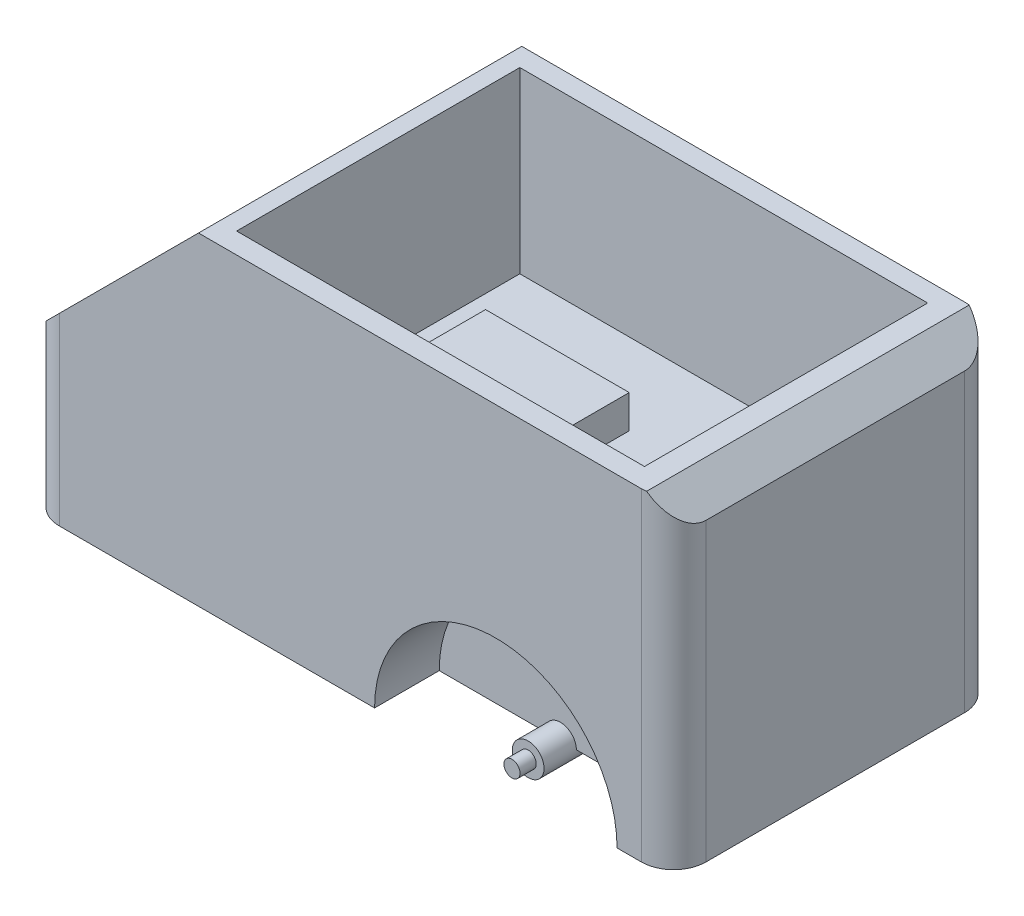
SolidWorks part; units mm, degrees
ref_plane "Front Plane" through (0, 0, 0) normal (0, 0, 1) x (1, 0, 0)
ref_plane "Top Plane" through (0, 0, 0) normal (0, 1, 0) x (1, 0, 0)
ref_plane "Right Plane" through (0, 0, 0) normal (1, 0, 0) x (0, 0, -1)
sketch "Sketch1" plane through (0, 0, 0) normal (0, 1, 0) x (1, 0, 0)
  line L1 (-91.44, 50.8) -> (91.44, 50.8)
  line L2 (-101.6, 40.64) -> (-101.6, -40.64)
  line L3 (-91.44, -50.8) -> (91.44, -50.8)
  line L4 (101.6, 40.64) -> (101.6, -40.64)
  line L5 (-101.6, 50.8) -> (101.6, -50.8) construction
  line L6 (-101.6, -50.8) -> (101.6, 50.8) construction
  arc A0 (91.44, 50.8) -> (101.6, 40.64) centre (91.44, 40.64) cw
  arc A1 (91.44, -50.8) -> (101.6, -40.64) centre (91.44, -40.64) ccw
  arc A2 (-101.6, -40.64) -> (-91.44, -50.8) centre (-91.44, -40.64) ccw
  arc A3 (-91.44, 50.8) -> (-101.6, 40.64) centre (-91.44, 40.64) ccw
  point P0 (0, 0)
  dimension "D1" = 10.16
extrude "Boss-Extrude1" add sketch "Sketch1" along normal blind 101.6
sketch "Sketch4" plane through (0, 0, -50.8) normal (0, 0, -1) x (-1, 0, 0)
  line L0 (-91.44, 0) -> (91.44, 0) construction
  circle A0 centre (-45.7162, 0) radius 38.1
extrude "Cut-Extrude1" cut sketch "Sketch4" against normal blind 20.32
mirror "Mirror1" about plane through (0, 0, 0) normal (0, 0, 1) of "Cut-Extrude1"
sketch "Sketch5" plane through (0, 0, -30.48) normal (0, 0, -1) x (-1, 0, 0)
  line L0 (-7.6162, 0) -> (-83.8162, 0) construction
  circle A0 centre (-45.7162, 0) radius 4.9938
extrude "Boss-Extrude3" add sketch "Sketch5" against normal blind 71.12 and the other way blind 10.16 contours A0
sketch "Sketch6" plane through (0, 0, -40.64) normal (0, 0, -1) x (-1, 0, 0)
  circle A0 centre (-45.7162, 0) radius 2.54
extrude "Boss-Extrude4" add sketch "Sketch6" against normal blind 86.36 and the other way blind 5.08
sketch "Sketch8" plane through (0, 0, 0) normal (0, 1, 0) x (1, 0, 0)
  circle A0 centre (-63.7754, 0) radius 19.05
  dimension "D1" = 38.1
extrude "Cut-Extrude2" cut sketch "Sketch8" along normal blind 3.175
ref_plane "Plane1" through (-101.6, 101.6, 0) normal (-0.7071, 0.7071, 0) x (0, 0, 1)
sketch "Sketch9" plane through (-101.6, 101.6, 0) normal (-0.7071, 0.7071, 0) x (0, 0, 1)
  line L1 (-102.2232, 151.2575) -> (102.2232, 151.2575)
  line L2 (-102.2232, 151.2575) -> (-102.2232, -60.7481)
  line L3 (-102.2232, -60.7481) -> (102.2232, -60.7481)
  line L4 (102.2232, 151.2575) -> (102.2232, -60.7481)
  line L5 (-102.2232, 151.2575) -> (102.2232, -60.7481) construction
  line L6 (-102.2232, -60.7481) -> (102.2232, 151.2575) construction
  point P0 (0, 45.2547)
extrude "Cut-Extrude3" cut sketch "Sketch9" against normal blind 38.1
ref_plane "Plane2" through (101.6, 101.6, 0) normal (-0.7071, -0.7071, 0) x (0, 0, -1)
sketch "Sketch10" plane through (101.6, 101.6, 0) normal (-0.7071, -0.7071, 0) x (0, 0, -1)
  line L1 (-95.9761, -34.9221) -> (95.9761, -34.9221)
  line L2 (-95.9761, -34.9221) -> (-95.9761, 123.6332)
  line L3 (-95.9761, 123.6332) -> (95.9761, 123.6332)
  line L4 (95.9761, -34.9221) -> (95.9761, 123.6332)
  line L5 (-95.9761, -34.9221) -> (95.9761, 123.6332) construction
  line L6 (-95.9761, 123.6332) -> (95.9761, -34.9221) construction
  point P0 (0, 44.3556)
extrude "Cut-Extrude4" cut sketch "Sketch10" along normal blind 6.096
sketch "Sketch11" plane through (0, 101.6, 0) normal (0, 1, 0) x (1, 0, 0)
  line L1 (-42.2597, 44.7167) -> (85.9055, 44.7167)
  line L2 (-42.2597, 44.7167) -> (-42.2597, -44.2734)
  line L3 (-42.2597, -44.2734) -> (85.9055, -44.2734)
  line L4 (85.9055, 44.7167) -> (85.9055, -44.2734)
extrude "Cut-Extrude5" cut sketch "Sketch11" against normal blind 56.134
sketch "Sketch12" plane through (0, 45.466, 0) normal (0, 1, 0) x (1, 0, 0)
  line L0 (85.9055, 44.7167) -> (-42.2597, 44.7167) construction
  line L1 (-27.4939, 19.1769) -> (17.6655, 19.1769)
  line L2 (-27.4939, 19.1769) -> (-27.4939, -22.7776)
  line L3 (-27.4939, -22.7776) -> (17.6655, -22.7776)
  line L4 (17.6655, 19.1769) -> (17.6655, -22.7776)
  line L5 (50.8795, 44.7167) -> (75.3529, 44.7167)
  line L6 (50.8795, 44.7167) -> (50.8795, 3.444)
  line L7 (50.8795, 3.444) -> (75.3529, 3.444)
  line L8 (75.3529, 44.7167) -> (75.3529, 3.444)
  line L9 (-42.2597, -44.2734) -> (85.9055, -44.2734) construction
  line L10 (50.8795, -5.5879) -> (75.3529, -5.5879)
  line L11 (50.8795, -5.5879) -> (50.8795, -44.2734)
  line L12 (50.8795, -44.2734) -> (75.3529, -44.2734)
  line L13 (75.3529, -5.5879) -> (75.3529, -44.2734)
extrude "Boss-Extrude5" add sketch "Sketch12" along normal blind 10.414
sketch "Sketch13" plane through (0, 55.88, 0) normal (0, 1, 0) x (1, 0, 0)
  text T0 "ARDUINO"
sketch "Sketch14" plane through (0, 55.88, 0) normal (0, 1, 0) x (1, 0, 0)
  text T0 "MOTOR-1"
sketch "Sketch15" plane through (0, 55.88, 0) normal (0, 1, 0) x (1, 0, 0)
  text T0 "MOTOR-2"
sketch "Sketch17" plane through (0, 101.6, 0) normal (0, 1, 0) x (1, 0, 0)
  line L1 (-44.6836, 47.5537) -> (89.3378, 47.5537)
  line L2 (-44.6836, 47.5537) -> (-44.6836, -47.4266)
  line L3 (-44.6836, -47.4266) -> (89.3378, -47.4266)
  line L4 (89.3378, 47.5537) -> (89.3378, -47.4266)
